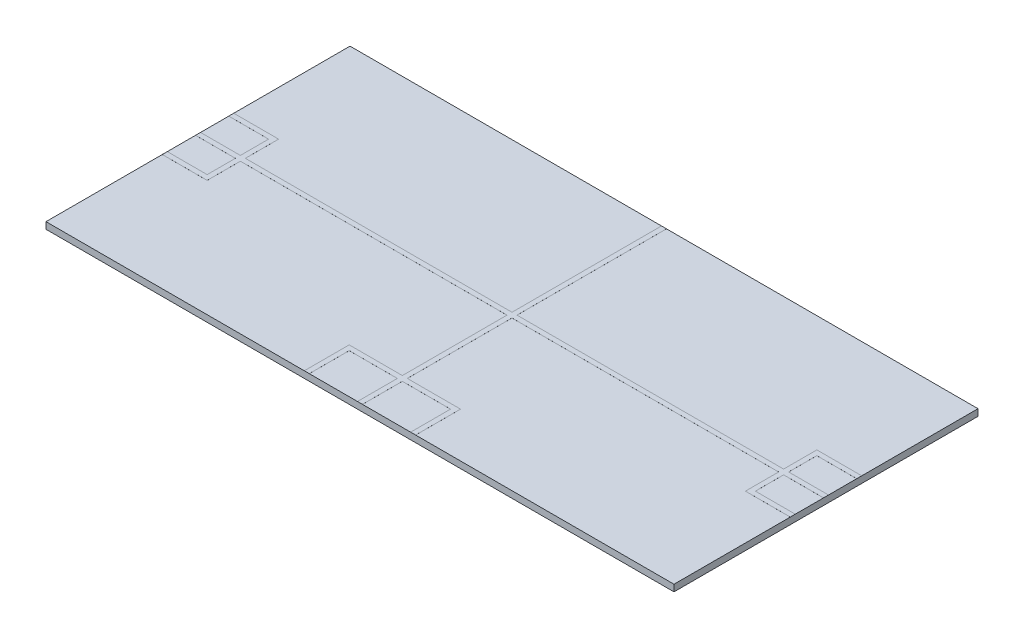
SolidWorks part; units mm, degrees
ref_plane "Front Plane" through (0, 0, 0) normal (0, 0, 1) x (1, 0, 0)
ref_plane "Top Plane" through (0, 0, 0) normal (0, 1, 0) x (1, 0, 0)
ref_plane "Right Plane" through (0, 0, 0) normal (1, 0, 0) x (0, 0, -1)
sketch "Sketch1" plane through (0, 0, 0) normal (0, 1, 0) x (1, 0, 0)
  line L1 (-1200.15, -581.025) -> (1200.15, -581.025)
  line L2 (-1200.15, -581.025) -> (-1200.15, 581.025)
  line L3 (-1200.15, 581.025) -> (1200.15, 581.025)
  line L4 (1200.15, -581.025) -> (1200.15, 581.025)
  line L5 (-1200.15, -581.025) -> (1200.15, 581.025) construction
  line L6 (-1200.15, 581.025) -> (1200.15, -581.025) construction
  point P0 (0, 0)
  dimension "D1" = 2400.3
  dimension "D2" = 1162.05
extrude "Boss-Extrude1" add sketch "Sketch1" along normal blind 25.4
sketch "Sketch2" plane through (0, 25.4, 0) normal (0, 1, 0) x (1, 0, 0)
  line L0 (-1200.15, 136.525) -> (-1028.7, 136.525)
  line L1 (-1200.15, 581.025) -> (-1200.15, -581.025) construction
  line L2 (-1028.7, 136.525) -> (-1028.7, 9.525)
  line L3 (-1028.7, 9.525) -> (-9.525, 9.525)
  line L4 (-9.525, 9.525) -> (-9.525, 581.025)
  line L5 (1200.15, 581.025) -> (-1200.15, 581.025) construction
  line L6 (-9.525, 581.025) -> (9.525, 581.025)
  line L7 (9.525, 581.025) -> (9.525, 9.525)
  line L8 (9.525, 9.525) -> (1028.7, 9.525)
  line L9 (1028.7, 9.525) -> (1028.7, 136.525)
  line L10 (1028.7, 136.525) -> (1200.15, 136.525)
  line L11 (1200.15, -581.025) -> (1200.15, 581.025) construction
  line L12 (1200.15, 136.525) -> (1200.15, 117.475)
  line L13 (1200.15, 117.475) -> (1047.75, 117.475)
  line L14 (1047.75, 117.475) -> (1047.75, 9.525)
  line L15 (1047.75, 9.525) -> (1200.15, 9.525)
  line L16 (1200.15, 9.525) -> (1200.15, -9.525)
  line L17 (1200.15, -9.525) -> (1047.75, -9.525)
  line L18 (1047.75, -9.525) -> (1047.75, -117.475)
  line L19 (1047.75, -117.475) -> (1200.15, -117.475)
  line L20 (1200.15, -117.475) -> (1200.15, -136.525)
  line L22 (1200.15, -136.525) -> (1028.7, -136.525)
  line L23 (1028.7, -136.525) -> (1028.7, -9.525)
  line L24 (1028.7, -9.525) -> (9.525, -9.525)
  line L25 (-9.525, -9.525) -> (-9.525, -409.575)
  line L27 (-9.525, -409.575) -> (-212.725, -409.575)
  line L28 (-212.725, -409.575) -> (-212.725, -581.025)
  line L29 (-9.525, -9.525) -> (-1028.7, -9.525)
  line L30 (-1028.7, -9.525) -> (-1028.7, -136.525)
  line L31 (-1028.7, -136.525) -> (-1200.15, -136.525)
  line L32 (-1200.15, -136.525) -> (-1200.15, -117.475)
  line L33 (-1200.15, -117.475) -> (-1047.75, -117.475)
  line L34 (-1047.75, -117.475) -> (-1047.75, -9.525)
  line L35 (-1047.75, -9.525) -> (-1200.15, -9.525)
  line L36 (-1200.15, -9.525) -> (-1200.15, 9.525)
  line L37 (-1200.15, 9.525) -> (-1047.75, 9.525)
  line L38 (-1047.75, 9.525) -> (-1047.75, 117.475)
  line L39 (-1047.75, 117.475) -> (-1200.15, 117.475)
  line L40 (-1200.15, 117.475) -> (-1200.15, 136.525)
  line L41 (-1200.15, -581.025) -> (1200.15, -581.025) construction
  line L42 (-212.725, -581.025) -> (-193.675, -581.025)
  line L43 (-193.675, -581.025) -> (-193.675, -428.625)
  line L44 (-193.675, -428.625) -> (-9.525, -428.625)
  line L45 (-9.525, -428.625) -> (-9.525, -581.025)
  line L46 (-9.525, -581.025) -> (9.525, -581.025)
  line L47 (9.525, -581.025) -> (9.525, -428.625)
  line L48 (9.525, -428.625) -> (193.675, -428.625)
  line L49 (193.675, -428.625) -> (193.675, -581.025)
  line L50 (193.675, -581.025) -> (212.725, -581.025)
  line L51 (212.725, -581.025) -> (212.725, -409.575)
  line L52 (212.725, -409.575) -> (9.525, -409.575)
  line L53 (9.525, -409.575) -> (9.525, -9.525)
  line L54 (-1200.15, 0) -> (1200.15, 0) construction
  point P4 (0, 0)
  point P58 (0, 0)
  dimension "D1" = 19.05
  dimension "D2" = 19.05
  dimension "D3" = 19.05
  dimension "D4" = 171.45
  dimension "D5" = 203.2
  dimension "D6" = 127
extrude "Boss-Extrude2" add sketch "Sketch2" along normal blind 0.127
